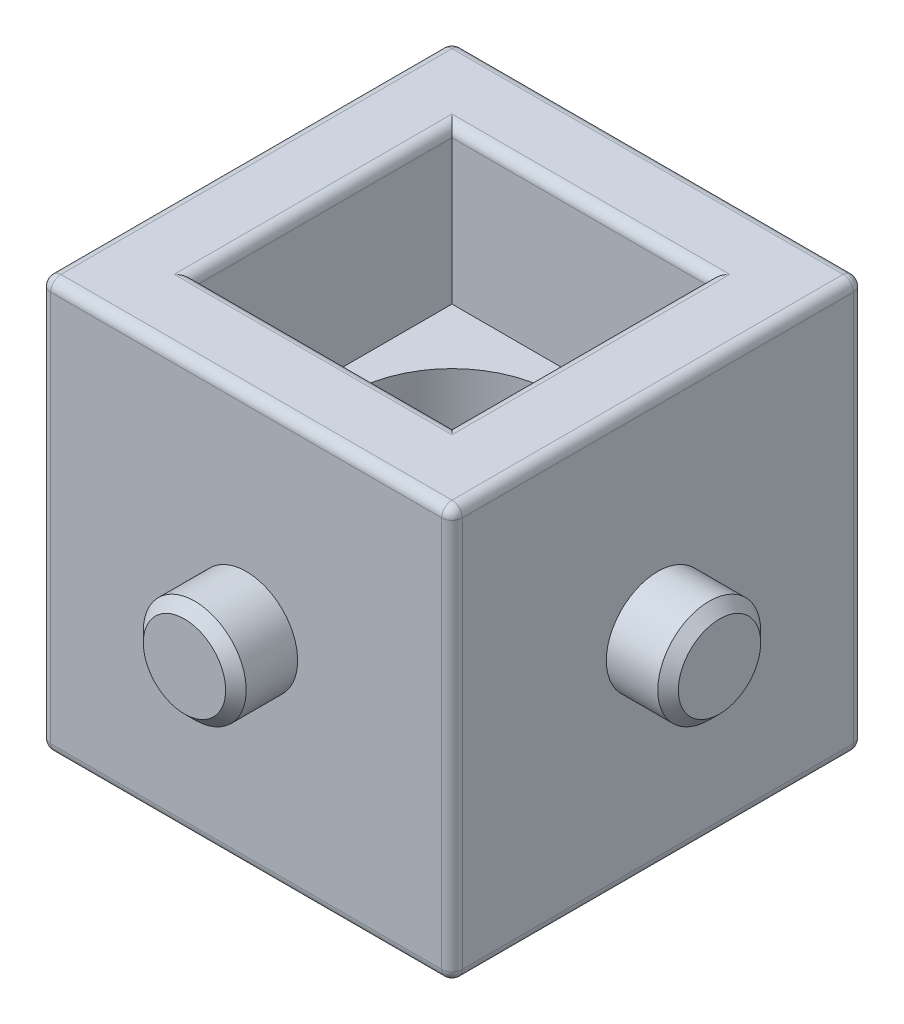
SolidWorks part; units mm, degrees
ref_plane "前视基准面" through (0, 0, 0) normal (0, 0, 1) x (1, 0, 0)
ref_plane "上视基准面" through (0, 0, 0) normal (0, 1, 0) x (1, 0, 0)
ref_plane "右视基准面" through (0, 0, 0) normal (1, 0, 0) x (0, 0, -1)
sketch "草图1" plane through (0, 0, 0) normal (0, 1, 0) x (1, 0, 0)
  line L0 (4, 4) -> (4, -4)
  line L1 (4, 4) -> (-4, 4)
  line L2 (4, -4) -> (-4, -4)
  line L3 (-4, 4) -> (-4, -4)
  line L4 (4, 4) -> (-4, -4) construction
  line L5 (4, -4) -> (-4, 4) construction
  point P1 (0, 0)
  dimension "D1" = 8
  dimension "D2" = 8
extrude "凸台-拉伸1" add sketch "草图1" along normal blind 8
sketch "草图2" plane through (0, 8, 0) normal (0, 1, 0) x (1, 0, 0)
  line L8 (2.5, 2.5) -> (-2.5, 2.5)
  line L9 (-2.5, 2.5) -> (-2.5, -2.5)
  line L10 (-2.5, -2.5) -> (2.5, -2.5)
  line L11 (2.5, -2.5) -> (2.5, 2.5)
  line L12 (2.5, 2.5) -> (-2.5, 2.5)
  line L13 (-2.5, 2.5) -> (-2.5, -2.5)
  line L14 (-2.5, -2.5) -> (2.5, -2.5)
  line L15 (2.5, -2.5) -> (2.5, 2.5)
  dimension "D1" = 1.5
extrude "切除-拉伸1" cut sketch "草图2" against normal blind 3
sketch "草图3" plane through (0, 0, 0) normal (0, -1, 0) x (1, 0, 0)
  line L8 (-2.5, -2.5) -> (2.5, -2.5)
  line L9 (2.5, -2.5) -> (2.5, 2.5)
  line L10 (2.5, 2.5) -> (-2.5, 2.5)
  line L11 (-2.5, 2.5) -> (-2.5, -2.5)
  line L12 (-2.5, -2.5) -> (2.5, -2.5)
  line L13 (2.5, -2.5) -> (2.5, 2.5)
  line L14 (2.5, 2.5) -> (-2.5, 2.5)
  line L15 (-2.5, 2.5) -> (-2.5, -2.5)
  dimension "D1" = 1.5
extrude "切除-拉伸2" cut sketch "草图3" against normal blind 3
sketch "草图4" plane through (0, 3, 0) normal (0, -1, 0) x (1, 0, 0)
  circle A0 centre (0, 0) radius 2
  dimension "D1" = 4
extrude "切除-拉伸3" cut sketch "草图4" against normal up to next
sketch "草图5" plane through (-4, 0, 0) normal (-1, 0, 0) x (0, 0, 1)
  line L0 (0, 0) -> (0, 4) construction
  circle A0 centre (0, 4) radius 1
  dimension "D2" = 2
  dimension "D1" = 4
extrude "凸台-拉伸2" add sketch "草图5" along normal blind 1.2
mirror "镜向1" about plane through (0, 0, 0) normal (1, 0, 0) of "凸台-拉伸2"
sketch "草图6" plane through (0, 0, -4) normal (0, 0, -1) x (-1, 0, 0)
  line L0 (0, 0) -> (0, 4) construction
  circle A0 centre (0, 4) radius 1
  dimension "D2" = 2
  dimension "D1" = 4
extrude "凸台-拉伸3" add sketch "草图6" along normal blind 1.2
mirror "镜向2" about plane through (0, 0, 0) normal (0, 0, 1) of "凸台-拉伸3"
chamfer "倒角1" distance 0.2 angle 45 4 edges at (-5.2, 4, 1) (-1, 4, -5.2) (-1, 4, 5.2) (5.2, 4, 1)
fillet "圆角1" radius 0.2 20 edges at (-4, 0, 0) (0, 0, 4) (4, 0, 0) (0, 0, -4) (2.5, 0, 0) (0, 0, 2.5) (-2.5, 0, 0) (0, 0, -2.5) (4, 8, 0) (0, 8, 4) (-4, 8, 0) (0, 8, -4) (0, 8, -2.5) (-2.5, 8, 0) (0, 8, 2.5) (2.5, 8, 0) (4, 4, 4) (4, 4, -4) (-4, 4, 4) (-4, 4, -4)
